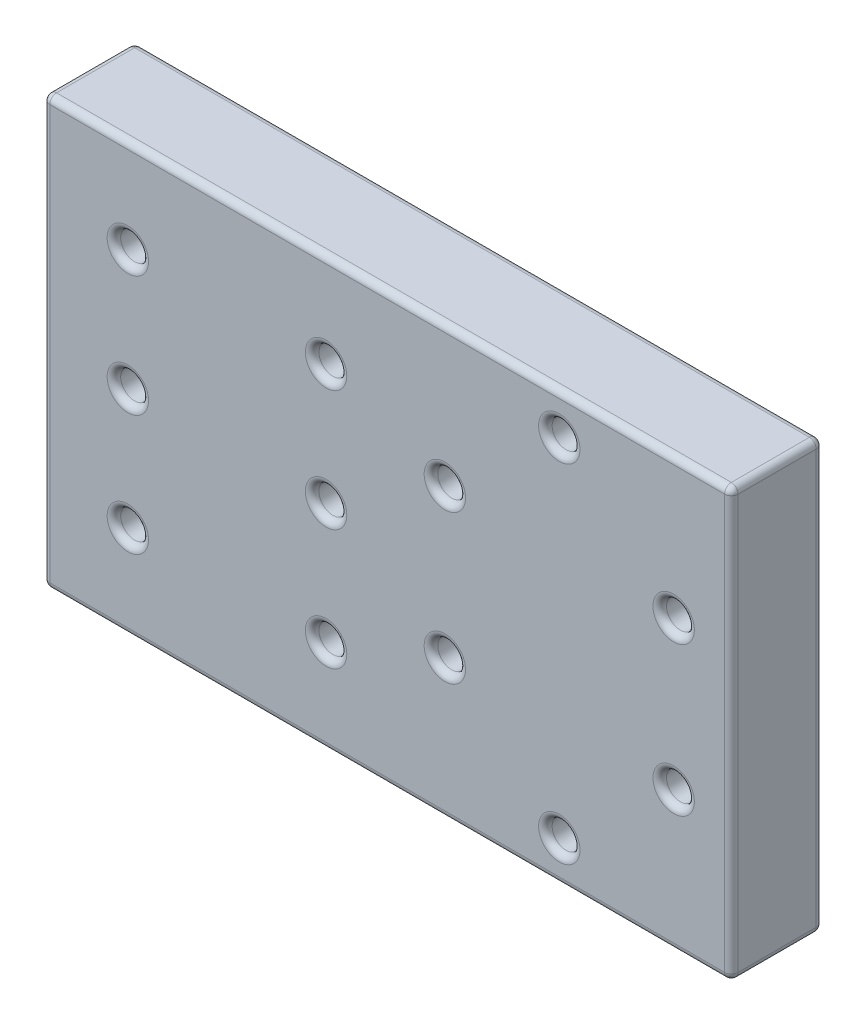
SolidWorks part; units mm, degrees
ref_plane "정면" through (0, 0, 0) normal (0, 0, 1) x (1, 0, 0)
ref_plane "윗면" through (0, 0, 0) normal (0, 1, 0) x (1, 0, 0)
ref_plane "우측면" through (0, 0, 0) normal (1, 0, 0) x (0, 0, -1)
sketch "스케치1" plane through (0, 0, 0) normal (0, 0, 1) x (1, 0, 0)
  line L1 (-50.7, 31.5) -> (50.7, 31.5)
  line L2 (-50.7, 31.5) -> (-50.7, -31.5)
  line L3 (-50.7, -31.5) -> (50.7, -31.5)
  line L4 (50.7, 31.5) -> (50.7, -31.5)
  point P4 (0, 31.5)
  point P6 (50.7, 0)
  dimension "D1" = 101.4
  dimension "D2" = 63
extrude "보스-돌출1" add sketch "스케치1" along normal blind 13.5
sketch "스케치2" plane through (0, 0, 13.5) normal (0, 0, 1) x (1, 0, 0)
  line L0 (-38.2, 17.75) -> (-9, 17.75) construction
  line L1 (-9, 17.75) -> (-9, -17.75) construction
  line L2 (-9, -17.75) -> (-38.2, -17.75) construction
  line L3 (-38.2, -17.75) -> (-38.2, 17.75) construction
  line L4 (8.5, -10.95) -> (42.2, -10.95) construction
  line L5 (42.2, -10.95) -> (42.2, 10.95) construction
  line L6 (42.2, 10.95) -> (8.5, 10.95) construction
  line L7 (8.5, 10.95) -> (8.5, -10.95) construction
  line L8 (8.5, 0) -> (42.2, 0) construction
  line L9 (25.35, 25.55) -> (25.35, -25.55) construction
  line L10 (-50.7, 31.5) -> (-50.7, -31.5) construction
  line L11 (50.7, -31.5) -> (50.7, 31.5) construction
  circle A0 centre (-38.2, 17.75) radius 2.05
  circle A1 centre (-38.2, 0) radius 2.05
  circle A2 centre (-38.2, -17.75) radius 2.05
  circle A3 centre (-9, 17.75) radius 2.05
  circle A4 centre (-9, 0) radius 2.05
  circle A5 centre (-9, -17.75) radius 2.05
  circle A6 centre (25.35, 25.55) radius 2.05
  circle A7 centre (8.5, 10.95) radius 2.05
  circle A8 centre (8.5, -10.95) radius 2.05
  circle A9 centre (42.2, 10.95) radius 2.05
  circle A10 centre (42.2, -10.95) radius 2.05
  circle A11 centre (25.35, -25.55) radius 2.05
  point P25 (-38.2, 0)
  point P27 (-9, 0)
  point P28 (25.35, 0)
  dimension "D1" = 4.1
  dimension "D2" = 35.5
  dimension "D3" = 29.2
  dimension "D4" = 12.5
  dimension "D5" = 33.7
  dimension "D6" = 21.9
  dimension "D7" = 51.1
  dimension "D8" = 8.5
extrude "컷-돌출1" cut sketch "스케치2" against normal blind 13.5
fillet "필렛1" radius 1 36 edges at (-50.7, -31.5, 6.75) (50.7, -31.5, 6.75) (50.7, 31.5, 6.75) (-50.7, 31.5, 6.75) (0, -31.5, 0) (50.7, 0, 0) (0, 31.5, 0) (-50.7, 0, 0) (-36.15, 17.75, 0) (27.4, 25.55, 0) (10.55, 10.95, 0) (10.55, -10.95, 0) (44.25, 10.95, 0) (44.25, -10.95, 0) (27.4, -25.55, 0) (-6.95, -17.75, 0) (-6.95, 0, 0) (-6.95, 17.75, 0) (-36.15, -17.75, 0) (-36.15, 0, 0) (0, 31.5, 13.5) (50.7, 0, 13.5) (0, -31.5, 13.5) (-50.7, 0, 13.5) (-36.15, 17.75, 13.5) (27.4, 25.55, 13.5) (10.55, 10.95, 13.5) (10.55, -10.95, 13.5) (44.25, 10.95, 13.5) (44.25, -10.95, 13.5) (27.4, -25.55, 13.5) (-6.95, -17.75, 13.5) (-6.95, 0, 13.5) (-6.95, 17.75, 13.5) (-36.15, -17.75, 13.5) (-36.15, 0, 13.5)
